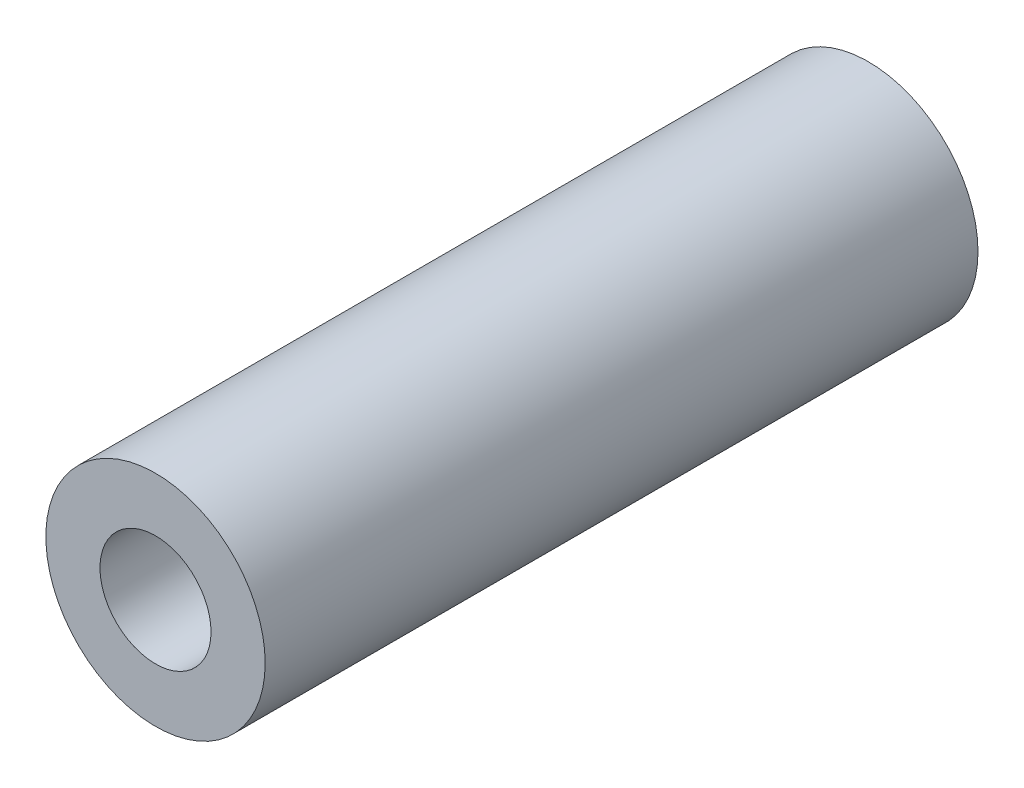
SolidWorks part; units mm, degrees
ref_plane "Front Plane" through (0, 0, 0) normal (0, 0, 1) x (1, 0, 0)
ref_plane "Top Plane" through (0, 0, 0) normal (0, 1, 0) x (1, 0, 0)
ref_plane "Right Plane" through (0, 0, 0) normal (1, 0, 0) x (0, 0, -1)
sketch "S01 - Solid post blank - 16 mm" plane through (0, 0, 0) normal (0, 0, 1) x (1, 0, 0)
  circle A0 centre (0, 0) radius 8
extrude "01 - Solid post blank - 16 mm" add sketch "S01 - Solid post blank - 16 mm" along normal blind 52
sketch "S02 - Rear M6 heat-set insert seat" plane through (0, 0, 0) normal (0, 0, 1) x (1, 0, 0)
  circle A0 centre (0, 0) radius 4.05
extrude "02 - Rear M6 heat-set insert seat" cut sketch "S02 - Rear M6 heat-set insert seat" along normal blind 14.35 from offset 0.1 offset against normal yes
sketch "S03 - Front M6 heat-set insert seat" plane through (0, 0, 0) normal (0, 0, 1) x (1, 0, 0)
  circle A0 centre (0, 0) radius 4.05
extrude "03 - Front M6 heat-set insert seat" cut sketch "S03 - Front M6 heat-set insert seat" along normal blind 14.35 from offset 37.75
